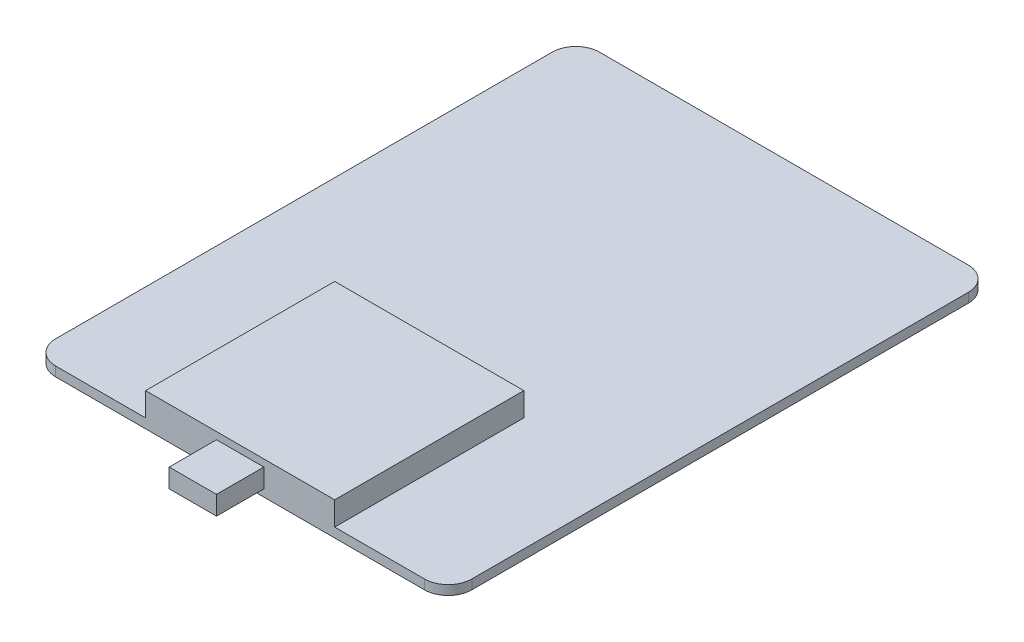
SolidWorks part; units mm, degrees
ref_plane "Front Plane" through (0, 0, 0) normal (0, 0, 1) x (1, 0, 0)
ref_plane "Top Plane" through (0, 0, 0) normal (0, 1, 0) x (1, 0, 0)
ref_plane "Right Plane" through (0, 0, 0) normal (1, 0, 0) x (0, 0, -1)
sketch "Sketch5" plane through (0, 0, 0) normal (0, 1, 0) x (1, 0, 0)
  line L1 (39, 57.5) -> (-39, 57.5)
  line L2 (44, 52.5) -> (44, -52.5)
  line L3 (39, -57.5) -> (-39, -57.5)
  line L4 (-44, 52.5) -> (-44, -52.5)
  line L5 (44, 57.5) -> (-44, -57.5) construction
  line L6 (44, -57.5) -> (-44, 57.5) construction
  arc A0 (-39, 57.5) -> (-44, 52.5) centre (-39, 52.5) ccw
  arc A1 (39, 57.5) -> (44, 52.5) centre (39, 52.5) cw
  arc A2 (44, -52.5) -> (39, -57.5) centre (39, -52.5) cw
  arc A3 (-39, -57.5) -> (-44, -52.5) centre (-39, -52.5) cw
  point P0 (0, 0)
  dimension "D3" = 5
  dimension "D1" = 88
  dimension "D2" = 115
extrude "Boss-Extrude4" add sketch "Sketch5" along normal blind 2
sketch "Sketch6" plane through (0, 2, 0) normal (0, 1, 0) x (1, 0, 0)
  line L0 (-39, -57.5) -> (39, -57.5) construction
  line L1 (20, -57.5) -> (-20, -57.5)
  line L2 (20, -57.5) -> (20, -17.5)
  line L3 (20, -17.5) -> (-20, -17.5)
  line L4 (-20, -57.5) -> (-20, -17.5)
  dimension "D1" = 40
  dimension "D2" = 40
  dimension "D3" = 20
extrude "Boss-Extrude5" add sketch "Sketch6" along normal blind 5
sketch "Sketch7" plane through (0, 0, 57.5) normal (0, 0, 1) x (1, 0, 0)
  line L0 (-39, 0) -> (39, 0) construction
  line L1 (5, 5.5) -> (-5, 5.5)
  line L2 (5, 5.5) -> (5, 1.5)
  line L3 (5, 1.5) -> (-5, 1.5)
  line L4 (-5, 5.5) -> (-5, 1.5)
  line L5 (5, 5.5) -> (-5, 1.5) construction
  line L6 (5, 1.5) -> (-5, 5.5) construction
  line L7 (20, 7) -> (20, 2) construction
  point P0 (0, 3.5)
  dimension "D1" = 4
  dimension "D2" = 3.5
  dimension "D3" = 10
  dimension "D4" = 15
extrude "Boss-Extrude6" add sketch "Sketch7" along normal blind 10
